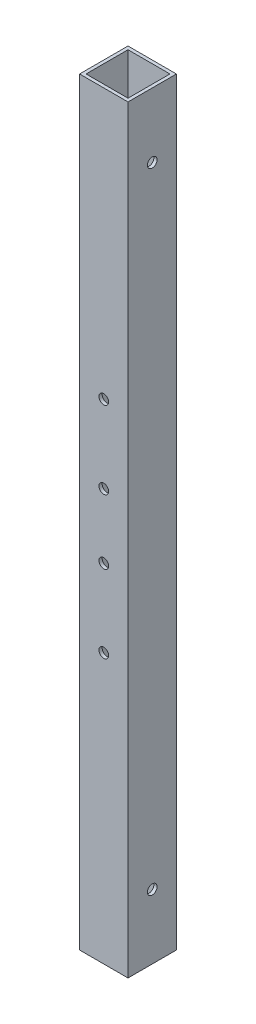
SolidWorks part; units mm, degrees
material "6061-O (SS)"
ref_plane "前视基准面" through (0, 0, 0) normal (0, 0, 1) x (1, 0, 0)
ref_plane "上视基准面" through (0, 0, 0) normal (0, 1, 0) x (1, 0, 0)
ref_plane "右视基准面" through (0, 0, 0) normal (1, 0, 0) x (0, 0, -1)
sketch "草图1" plane through (0, 0, 0) normal (0, 1, 0) x (1, 0, 0)
  line L1 (-7.5, -7.5) -> (7.5, -7.5)
  line L2 (-7.5, -7.5) -> (-7.5, 7.5)
  line L3 (-7.5, 7.5) -> (7.5, 7.5)
  line L4 (7.5, -7.5) -> (7.5, 7.5)
  line L5 (-7.5, -7.5) -> (7.5, 7.5) construction
  line L6 (-7.5, 7.5) -> (7.5, -7.5) construction
  line L7 (-6.5, -6.5) -> (6.5, -6.5)
  line L8 (-6.5, -6.5) -> (-6.5, 6.5)
  line L9 (-6.5, 6.5) -> (6.5, 6.5)
  line L10 (6.5, -6.5) -> (6.5, 6.5)
  line L11 (-6.5, -6.5) -> (6.5, 6.5) construction
  line L12 (-6.5, 6.5) -> (6.5, -6.5) construction
  point P0 (0, 0)
  point P6 (0, 0)
  dimension "D1" = 15
  dimension "D2" = 1
extrude "凸台-拉伸1" add sketch "草图1" along normal blind 235
sketch "草图2" plane through (0, 0, 7.5) normal (0, 0, 1) x (1, 0, 0)
  line L0 (-7.5, 117.5) -> (7.5, 117.5) construction
  line L1 (-7.5, 235) -> (-7.5, 0) construction
  line L2 (7.5, 235) -> (7.5, 0) construction
  line L3 (0, 235) -> (0, 0) construction
  line L4 (-7.5, 235) -> (7.5, 235) construction
  circle A0 centre (0, 127.5) radius 1.5
  circle A1 centre (0, 107.5) radius 1.5
  circle A2 centre (0, 151.5) radius 1.5
  circle A3 centre (0, 83.5) radius 1.5
  dimension "D1" = 24
  dimension "D2" = 20
  dimension "D3" = 3
extrude "切除-拉伸1" cut sketch "草图2" against normal through all
sketch "草图3" plane through (7.5, 0, 0) normal (1, 0, 0) x (0, 0, -1)
  line L0 (0, 235) -> (0, 0) construction
  line L1 (-7.5, 235) -> (7.5, 235) construction
  line L2 (-7.5, 117.5) -> (7.5, 117.5) construction
  line L3 (7.5, 235) -> (7.5, 0) construction
  line L4 (-7.5, 235) -> (-7.5, 0) construction
  line L5 (-7.5, 0) -> (7.5, 0) construction
  circle A0 centre (0, 215) radius 1.5
  circle A1 centre (0, 20) radius 1.5
  dimension "D1" = 3
  dimension "D2" = 20
extrude "切除-拉伸2" cut sketch "草图3" against normal through all
